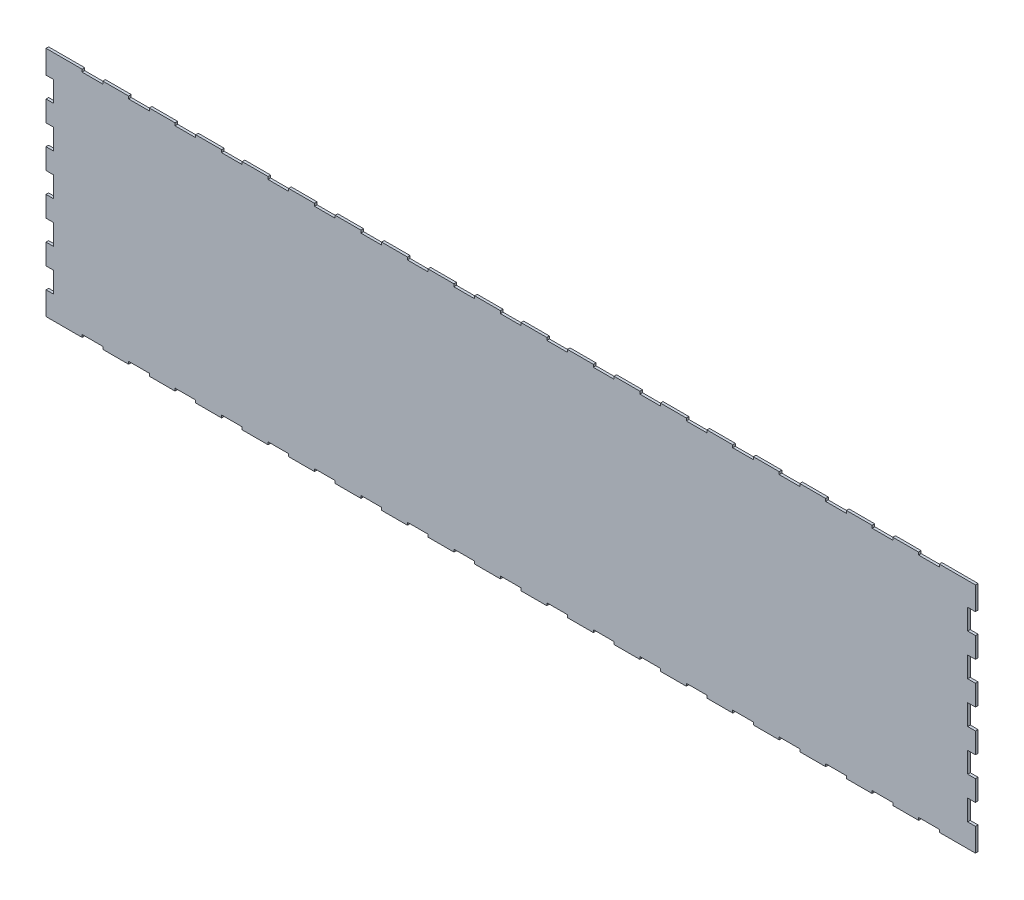
SolidWorks part; units mm, degrees
ref_plane "Front Plane" through (0, 0, 0) normal (0, 0, 1) x (1, 0, 0)
ref_plane "Top Plane" through (0, 0, 0) normal (0, 1, 0) x (1, 0, 0)
ref_plane "Right Plane" through (0, 0, 0) normal (1, 0, 0) x (0, 0, -1)
sketch "Sketch1" plane through (0, 0, 0) normal (0, 0, 1) x (1, 0, 0)
  line L0 (885, 100) -> (885, 60)
  line L1 (-900, 225) -> (-830, 225)
  line L2 (-900, 225) -> (-900, 180)
  line L4 (900, 225) -> (900, 180)
  line L5 (-900, 225) -> (900, -225) construction
  line L6 (-900, -225) -> (900, 225) construction
  line L7 (900, 180) -> (885, 180)
  line L9 (900, 140) -> (885, 140)
  line L10 (885, 180) -> (885, 140)
  line L11 (900, 100) -> (885, 100)
  line L12 (900, 60) -> (885, 60)
  line L13 (885, 20) -> (885, -20)
  line L14 (900, 20) -> (885, 20)
  line L15 (900, -20) -> (885, -20)
  line L16 (885, -60) -> (885, -100)
  line L17 (900, -60) -> (885, -60)
  line L18 (900, -100) -> (885, -100)
  line L19 (885, -140) -> (885, -180)
  line L20 (900, -140) -> (885, -140)
  line L21 (900, -180) -> (885, -180)
  line L22 (900, 60) -> (900, 20)
  line L23 (900, -20) -> (900, -60)
  line L24 (900, -100) -> (900, -140)
  line L25 (900, -180) -> (900, -225)
  line L26 (900, 140) -> (900, 100)
  line L27 (0, 0) -> (0, 140) construction
  line L28 (-900, -180) -> (-885, -180)
  line L29 (-900, -140) -> (-885, -140)
  line L30 (-885, -140) -> (-885, -180)
  line L31 (-900, -100) -> (-885, -100)
  line L32 (-900, -60) -> (-885, -60)
  line L33 (-885, -60) -> (-885, -100)
  line L34 (-900, -20) -> (-885, -20)
  line L35 (-900, 20) -> (-885, 20)
  line L36 (-885, 20) -> (-885, -20)
  line L37 (-900, 60) -> (-885, 60)
  line L38 (-900, 100) -> (-885, 100)
  line L39 (-885, 180) -> (-885, 140)
  line L40 (-900, 140) -> (-885, 140)
  line L41 (-900, 180) -> (-885, 180)
  line L42 (-885, 100) -> (-885, 60)
  line L43 (-900, 140) -> (-900, 100)
  line L44 (-900, 60) -> (-900, 20)
  line L45 (-900, -20) -> (-900, -60)
  line L46 (-900, -100) -> (-900, -140)
  line L47 (-900, -180) -> (-900, -225)
  line L48 (-790, -225) -> (-740, -225)
  line L49 (790, 225) -> (790, 220) construction
  line L50 (790, 220) -> (830, 220) construction
  line L51 (830, 220) -> (830, 225) construction
  line L52 (-700, -225) -> (-650, -225)
  line L53 (700, 225) -> (700, 220) construction
  line L54 (700, 220) -> (740, 220) construction
  line L55 (740, 220) -> (740, 225) construction
  line L56 (-610, -225) -> (-560, -225)
  line L57 (610, 225) -> (610, 220) construction
  line L58 (610, 220) -> (650, 220) construction
  line L59 (650, 220) -> (650, 225) construction
  line L60 (-520, -225) -> (-470, -225)
  line L61 (520, 225) -> (520, 220) construction
  line L62 (520, 220) -> (560, 220) construction
  line L63 (560, 220) -> (560, 225) construction
  line L64 (-430, -225) -> (-380, -225)
  line L65 (430, 225) -> (430, 220) construction
  line L66 (430, 220) -> (470, 220) construction
  line L67 (470, 220) -> (470, 225) construction
  line L68 (-340, -225) -> (-290, -225)
  line L69 (340, 225) -> (340, 220) construction
  line L70 (340, 220) -> (380, 220) construction
  line L71 (380, 220) -> (380, 225) construction
  line L72 (-250, -225) -> (-200, -225)
  line L73 (250, 225) -> (250, 220) construction
  line L74 (250, 220) -> (290, 220) construction
  line L75 (290, 220) -> (290, 225) construction
  line L76 (-160, -225) -> (-110, -225)
  line L77 (160, 225) -> (160, 220) construction
  line L78 (160, 220) -> (200, 220) construction
  line L79 (200, 220) -> (200, 225) construction
  line L80 (-70, -225) -> (-20, -225)
  line L81 (70, 225) -> (70, 220) construction
  line L82 (70, 220) -> (110, 220) construction
  line L83 (110, 220) -> (110, 225) construction
  line L84 (20, -225) -> (70, -225)
  line L85 (-20, 225) -> (-20, 220) construction
  line L86 (-20, 220) -> (20, 220) construction
  line L87 (20, 220) -> (20, 225) construction
  line L88 (110, -225) -> (160, -225)
  line L89 (-110, 225) -> (-110, 220) construction
  line L90 (-110, 220) -> (-70, 220) construction
  line L91 (-70, 220) -> (-70, 225) construction
  line L92 (200, -225) -> (250, -225)
  line L93 (-200, 225) -> (-200, 220) construction
  line L94 (-200, 220) -> (-160, 220) construction
  line L95 (-160, 220) -> (-160, 225) construction
  line L96 (290, -225) -> (340, -225)
  line L97 (-290, 225) -> (-290, 220) construction
  line L98 (-290, 220) -> (-250, 220) construction
  line L99 (-250, 220) -> (-250, 225) construction
  line L100 (380, -225) -> (430, -225)
  line L101 (-380, 225) -> (-380, 220) construction
  line L102 (-380, 220) -> (-340, 220) construction
  line L103 (-340, 220) -> (-340, 225) construction
  line L104 (470, -225) -> (520, -225)
  line L105 (-470, 225) -> (-470, 220) construction
  line L106 (-470, 220) -> (-430, 220) construction
  line L107 (-430, 220) -> (-430, 225) construction
  line L108 (560, -225) -> (610, -225)
  line L109 (-560, 225) -> (-560, 220) construction
  line L110 (-560, 220) -> (-520, 220) construction
  line L111 (-520, 220) -> (-520, 225) construction
  line L112 (650, -225) -> (700, -225)
  line L113 (-650, 225) -> (-650, 220) construction
  line L114 (-650, 220) -> (-610, 220) construction
  line L115 (-610, 220) -> (-610, 225) construction
  line L116 (740, -225) -> (790, -225)
  line L117 (-740, 225) -> (-740, 220) construction
  line L118 (-740, 220) -> (-700, 220) construction
  line L119 (-700, 220) -> (-700, 225) construction
  line L120 (830, -225) -> (900, -225)
  line L121 (-830, 225) -> (-830, 220) construction
  line L122 (-830, 220) -> (-790, 220) construction
  line L123 (-790, 220) -> (-790, 225) construction
  line L125 (790, 225) -> (790, 220)
  line L126 (790, 220) -> (830, 220)
  line L127 (830, 220) -> (830, 225)
  line L129 (700, 225) -> (700, 220)
  line L130 (700, 220) -> (740, 220)
  line L131 (740, 220) -> (740, 225)
  line L133 (610, 225) -> (610, 220)
  line L134 (610, 220) -> (650, 220)
  line L135 (650, 220) -> (650, 225)
  line L137 (520, 225) -> (520, 220)
  line L138 (520, 220) -> (560, 220)
  line L139 (560, 220) -> (560, 225)
  line L141 (430, 225) -> (430, 220)
  line L142 (430, 220) -> (470, 220)
  line L143 (470, 220) -> (470, 225)
  line L145 (340, 225) -> (340, 220)
  line L146 (340, 220) -> (380, 220)
  line L147 (380, 220) -> (380, 225)
  line L149 (250, 225) -> (250, 220)
  line L150 (250, 220) -> (290, 220)
  line L151 (290, 220) -> (290, 225)
  line L153 (160, 225) -> (160, 220)
  line L154 (160, 220) -> (200, 220)
  line L155 (200, 220) -> (200, 225)
  line L157 (70, 225) -> (70, 220)
  line L158 (70, 220) -> (110, 220)
  line L159 (110, 220) -> (110, 225)
  line L161 (-20, 225) -> (-20, 220)
  line L162 (-20, 220) -> (20, 220)
  line L163 (20, 220) -> (20, 225)
  line L165 (-110, 225) -> (-110, 220)
  line L166 (-110, 220) -> (-70, 220)
  line L167 (-70, 220) -> (-70, 225)
  line L169 (-200, 225) -> (-200, 220)
  line L170 (-200, 220) -> (-160, 220)
  line L171 (-160, 220) -> (-160, 225)
  line L173 (-290, 225) -> (-290, 220)
  line L174 (-290, 220) -> (-250, 220)
  line L175 (-250, 220) -> (-250, 225)
  line L177 (-380, 225) -> (-380, 220)
  line L178 (-380, 220) -> (-340, 220)
  line L179 (-340, 220) -> (-340, 225)
  line L181 (-470, 225) -> (-470, 220)
  line L182 (-470, 220) -> (-430, 220)
  line L183 (-430, 220) -> (-430, 225)
  line L185 (-560, 225) -> (-560, 220)
  line L186 (-560, 220) -> (-520, 220)
  line L187 (-520, 220) -> (-520, 225)
  line L189 (-650, 225) -> (-650, 220)
  line L190 (-650, 220) -> (-610, 220)
  line L191 (-610, 220) -> (-610, 225)
  line L193 (-740, 225) -> (-740, 220)
  line L194 (-740, 220) -> (-700, 220)
  line L195 (-700, 220) -> (-700, 225)
  line L197 (-830, 225) -> (-830, 220)
  line L198 (-830, 220) -> (-790, 220)
  line L199 (-790, 220) -> (-790, 225)
  line L200 (830, 225) -> (900, 225)
  line L201 (740, 225) -> (790, 225)
  line L202 (650, 225) -> (700, 225)
  line L203 (560, 225) -> (610, 225)
  line L204 (470, 225) -> (520, 225)
  line L205 (380, 225) -> (430, 225)
  line L206 (290, 225) -> (340, 225)
  line L207 (200, 225) -> (250, 225)
  line L208 (110, 225) -> (160, 225)
  line L209 (20, 225) -> (70, 225)
  line L210 (-70, 225) -> (-20, 225)
  line L211 (-160, 225) -> (-110, 225)
  line L212 (-250, 225) -> (-200, 225)
  line L213 (-340, 225) -> (-290, 225)
  line L214 (-430, 225) -> (-380, 225)
  line L215 (-520, 225) -> (-470, 225)
  line L216 (-610, 225) -> (-560, 225)
  line L217 (-700, 225) -> (-650, 225)
  line L218 (-790, 225) -> (-740, 225)
  line L219 (0, 0) -> (226.4615, 0) construction
  line L220 (-740, -225) -> (-740, -220)
  line L222 (-830, -225) -> (-830, -220)
  line L223 (-830, -220) -> (-790, -220)
  line L224 (-790, -225) -> (-790, -220)
  line L225 (-700, -225) -> (-700, -220)
  line L226 (-740, -220) -> (-700, -220)
  line L227 (-650, -225) -> (-650, -220)
  line L228 (-610, -225) -> (-610, -220)
  line L229 (-650, -220) -> (-610, -220)
  line L230 (-560, -225) -> (-560, -220)
  line L231 (-520, -225) -> (-520, -220)
  line L232 (-560, -220) -> (-520, -220)
  line L233 (-470, -225) -> (-470, -220)
  line L234 (-430, -225) -> (-430, -220)
  line L235 (-470, -220) -> (-430, -220)
  line L236 (-380, -225) -> (-380, -220)
  line L237 (-340, -225) -> (-340, -220)
  line L238 (-380, -220) -> (-340, -220)
  line L239 (-290, -225) -> (-290, -220)
  line L240 (-250, -225) -> (-250, -220)
  line L241 (-290, -220) -> (-250, -220)
  line L242 (-200, -225) -> (-200, -220)
  line L243 (-160, -225) -> (-160, -220)
  line L244 (-200, -220) -> (-160, -220)
  line L245 (-110, -225) -> (-110, -220)
  line L246 (-70, -225) -> (-70, -220)
  line L247 (-110, -220) -> (-70, -220)
  line L248 (-20, -225) -> (-20, -220)
  line L249 (20, -225) -> (20, -220)
  line L250 (-20, -220) -> (20, -220)
  line L251 (70, -225) -> (70, -220)
  line L252 (110, -225) -> (110, -220)
  line L253 (70, -220) -> (110, -220)
  line L254 (160, -225) -> (160, -220)
  line L255 (200, -225) -> (200, -220)
  line L256 (160, -220) -> (200, -220)
  line L257 (250, -225) -> (250, -220)
  line L258 (290, -225) -> (290, -220)
  line L259 (250, -220) -> (290, -220)
  line L260 (340, -225) -> (340, -220)
  line L261 (380, -225) -> (380, -220)
  line L262 (340, -220) -> (380, -220)
  line L263 (430, -225) -> (430, -220)
  line L264 (470, -225) -> (470, -220)
  line L265 (430, -220) -> (470, -220)
  line L266 (520, -225) -> (520, -220)
  line L267 (560, -225) -> (560, -220)
  line L268 (520, -220) -> (560, -220)
  line L269 (610, -225) -> (610, -220)
  line L270 (650, -225) -> (650, -220)
  line L271 (610, -220) -> (650, -220)
  line L272 (700, -225) -> (700, -220)
  line L273 (740, -225) -> (740, -220)
  line L274 (700, -220) -> (740, -220)
  line L275 (790, -225) -> (790, -220)
  line L276 (830, -225) -> (830, -220)
  line L277 (790, -220) -> (830, -220)
  line L278 (-900, -225) -> (-830, -225)
  point P0 (0, 0)
  dimension "D1" = 40
  dimension "D2" = 70
  dimension "D3" = 15
  dimension "D5" = 40
  dimension "D7" = 19
  dimension "D6" = 5
extrude "Boss-Extrude1" add sketch "Sketch1" along normal blind 5 contours L47 L278 L222 L223 L224 L48 L220 L226 L225 L52 L227 L229 L228 L56 L230 L232 L231 L60 L233 L235 L234 L64 L236 L238 L237 L68 L239 L241 L240 L72 L242 L244 L243 L76 L245 L247 L246 L80 L248 L250 L249 L84 L251 L253 L252 L88 L254 L256 L255 L92 L257
